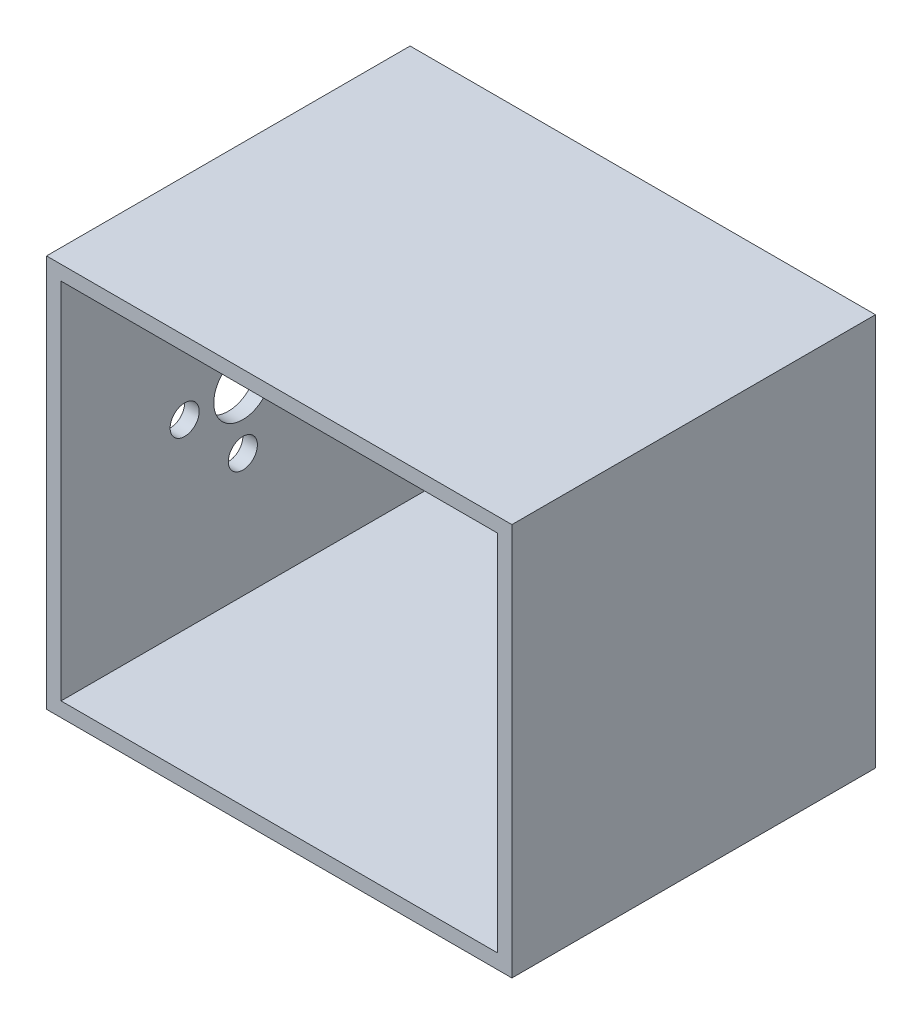
SolidWorks part; units mm, degrees
ref_plane "Ön Düzlem" through (0, 0, 0) normal (0, 0, 1) x (1, 0, 0)
ref_plane "Üst Düzlem" through (0, 0, 0) normal (0, 1, 0) x (1, 0, 0)
ref_plane "Sağ Düzlem" through (0, 0, 0) normal (1, 0, 0) x (0, 0, -1)
sketch "Çizim1" plane through (0, 0, 0) normal (0, 0, 1) x (1, 0, 0)
  line L1 (0, 0) -> (60, 0)
  line L2 (0, 0) -> (0, 50)
  line L3 (0, 50) -> (60, 50)
  line L4 (60, 0) -> (60, 50)
  dimension "D1" = 50
  dimension "D2" = 60
extrude "Ekstrüzyon-İnce1" add sketch "Çizim1" along normal blind 50 thin
sketch "Çizim2" plane through (-2, 0, 0) normal (-1, 0, 0) x (0, 0, 1)
  circle A0 centre (25, 25) radius 4
  circle A1 centre (33, 25) radius 2
  circle A2 centre (17, 25) radius 2
  circle A3 centre (25, 33) radius 2
  circle A4 centre (25, 17) radius 2
  dimension "D1" = 8
  dimension "D2" = 4
  dimension "D3" = 8
  dimension "D4" = 4
  dimension "D5" = 8
extrude "Kes-Ekstrüzyon1" cut sketch "Çizim2" against normal up to next
